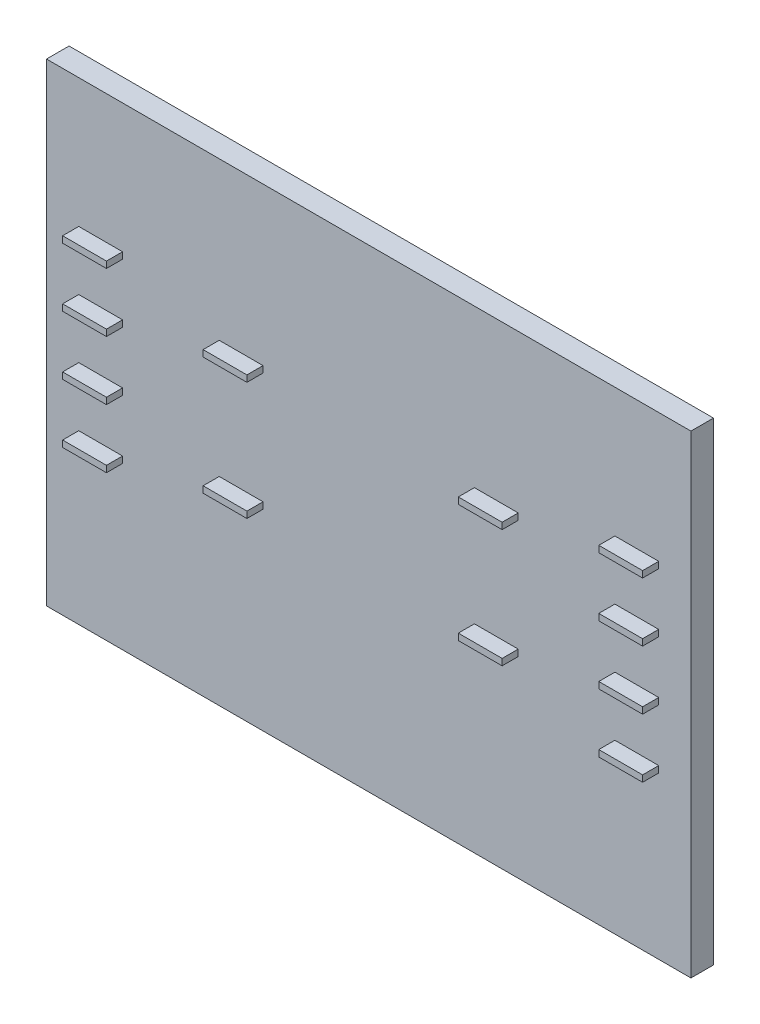
SolidWorks part; units mm, degrees
ref_plane "Front Plane" through (0, 0, 0) normal (0, 0, 1) x (1, 0, 0)
ref_plane "Top Plane" through (0, 0, 0) normal (0, 1, 0) x (1, 0, 0)
ref_plane "Right Plane" through (0, 0, 0) normal (1, 0, 0) x (0, 0, -1)
sketch "Sketch1" plane through (0, 0, 0) normal (0, 0, 1) x (1, 0, 0)
  line L1 (-248.7192, 164.2611) -> (-48.7192, 164.2611)
  line L2 (-248.7192, 164.2611) -> (-248.7192, 14.2611)
  line L3 (-248.7192, 14.2611) -> (-48.7192, 14.2611)
  line L4 (-48.7192, 164.2611) -> (-48.7192, 14.2611)
  dimension "D1" = 200
  dimension "D2" = 150
extrude "Boss-Extrude1" add sketch "Sketch1" along normal blind 7
sketch "Sketch2" plane through (0, 0, 7) normal (0, 0, 1) x (1, 0, 0)
  line L37 (-115.9192, 115.4611) -> (-115.9192, 113.4611)
  line L50 (-48.7192, 14.2611) -> (-48.7192, 164.2611) construction
  line L51 (-58.7192, 105.9611) -> (-58.7192, 103.9611)
  line L68 (-48.7192, 164.2611) -> (-58.7192, 164.2611) construction
  line L69 (-48.7192, 164.2611) -> (-248.7192, 164.2611) construction
  line L70 (-58.7192, 164.2611) -> (-58.7192, 14.2611) construction
  line L75 (-248.7192, 14.2611) -> (-48.7192, 14.2611) construction
  line L76 (-48.7192, 124.2611) -> (-248.7192, 124.2611) construction
  line L81 (-58.7192, 105.9611) -> (-72.3192, 105.9611)
  line L82 (-58.7192, 124.2611) -> (-72.3192, 124.2611)
  line L83 (-58.7192, 124.2611) -> (-58.7192, 122.2611)
  line L84 (-58.7192, 122.2611) -> (-72.3192, 122.2611)
  line L85 (-72.3192, 124.2611) -> (-72.3192, 122.2611)
  line L86 (-72.3192, 105.9611) -> (-72.3192, 103.9611)
  line L87 (-58.7192, 103.9611) -> (-72.3192, 103.9611)
  line L88 (-58.7192, 87.6611) -> (-58.7192, 85.6611)
  line L89 (-58.7192, 87.6611) -> (-72.3192, 87.6611)
  line L90 (-72.3192, 87.6611) -> (-72.3192, 85.6611)
  line L91 (-58.7192, 85.6611) -> (-72.3192, 85.6611)
  line L92 (-58.7192, 69.3611) -> (-58.7192, 67.3611)
  line L93 (-58.7192, 69.3611) -> (-72.3192, 69.3611)
  line L94 (-72.3192, 69.3611) -> (-72.3192, 67.3611)
  line L95 (-58.7192, 67.3611) -> (-72.3192, 67.3611)
  line L96 (-248.7192, 164.2611) -> (-248.7192, 14.2611) construction
  line L97 (-238.7192, 105.9611) -> (-238.7192, 103.9611)
  line L98 (-238.7192, 124.2611) -> (-225.1192, 124.2611)
  line L99 (-238.7192, 124.2611) -> (-238.7192, 122.2611)
  line L100 (-238.7192, 122.2611) -> (-225.1192, 122.2611)
  line L101 (-225.1192, 124.2611) -> (-225.1192, 122.2611)
  line L102 (-238.7192, 105.9611) -> (-225.1192, 105.9611)
  line L103 (-225.1192, 105.9611) -> (-225.1192, 103.9611)
  line L104 (-238.7192, 103.9611) -> (-225.1192, 103.9611)
  line L105 (-238.7192, 87.6611) -> (-238.7192, 85.6611)
  line L106 (-238.7192, 87.6611) -> (-225.1192, 87.6611)
  line L107 (-225.1192, 87.6611) -> (-225.1192, 85.6611)
  line L108 (-238.7192, 85.6611) -> (-225.1192, 85.6611)
  line L109 (-238.7192, 69.3611) -> (-238.7192, 67.3611)
  line L110 (-238.7192, 69.3611) -> (-225.1192, 69.3611)
  line L111 (-225.1192, 69.3611) -> (-225.1192, 67.3611)
  line L112 (-238.7192, 67.3611) -> (-225.1192, 67.3611)
  line L113 (-195.1192, 115.4611) -> (-181.5192, 115.4611)
  line L114 (-195.1192, 115.4611) -> (-195.1192, 113.4611)
  line L115 (-195.1192, 113.4611) -> (-181.5192, 113.4611)
  line L116 (-181.5192, 115.4611) -> (-181.5192, 113.4611)
  line L117 (-115.9192, 115.4611) -> (-102.3192, 115.4611)
  line L118 (-102.3192, 115.4611) -> (-102.3192, 113.4611)
  line L119 (-115.9192, 113.4611) -> (-102.3192, 113.4611)
  line L120 (-195.1192, 78.8611) -> (-195.1192, 76.8611)
  line L121 (-195.1192, 78.8611) -> (-181.5192, 78.8611)
  line L122 (-181.5192, 78.8611) -> (-181.5192, 76.8611)
  line L123 (-195.1192, 76.8611) -> (-181.5192, 76.8611)
  line L125 (-102.3192, 76.8611) -> (-115.9192, 76.8611)
  line L126 (-102.3192, 76.8611) -> (-102.3192, 78.8611)
  line L127 (-102.3192, 78.8611) -> (-115.9192, 78.8611)
  line L128 (-115.9192, 76.8611) -> (-115.9192, 78.8611)
  point P7 (-48.7192, 124.2611)
  point P10 (-58.7192, 124.2611)
  dimension "D1" = 10
  dimension "D2" = 40
  dimension "D3" = 10
  dimension "D4" = 2
  dimension "D7" = 13.6
  dimension "D5" = 2
  dimension "D6" = 13.6
  dimension "D8" = 40
  dimension "D9" = 10
  dimension "D10" = 4
  dimension "D12" = 16.3
  dimension "D13" = 2
  dimension "D14" = 13.6
  dimension "D15" = 6.8
  dimension "D16" = 30
  dimension "D18" = 30
  dimension "D20" = 6.8
  dimension "D21" = 2
  dimension "D22" = 30
  dimension "D11" = 4
  dimension "D17" = 2
  dimension "D19" = 2
extrude "Boss-Extrude2" add sketch "Sketch2" along normal blind 5
sketch "Sketch3" plane through (0, 14.2611, 0) normal (0, -1, 0) x (1, 0, 0)
  line L1 (-248.7192, 7) -> (-48.7192, 7)
  line L2 (-248.7192, 7) -> (-248.7192, 0)
  line L3 (-248.7192, 0) -> (-48.7192, 0)
  line L4 (-48.7192, 7) -> (-48.7192, 0)
extrude "Cut-Extrude1" cut sketch "Sketch3" against normal blind 3
